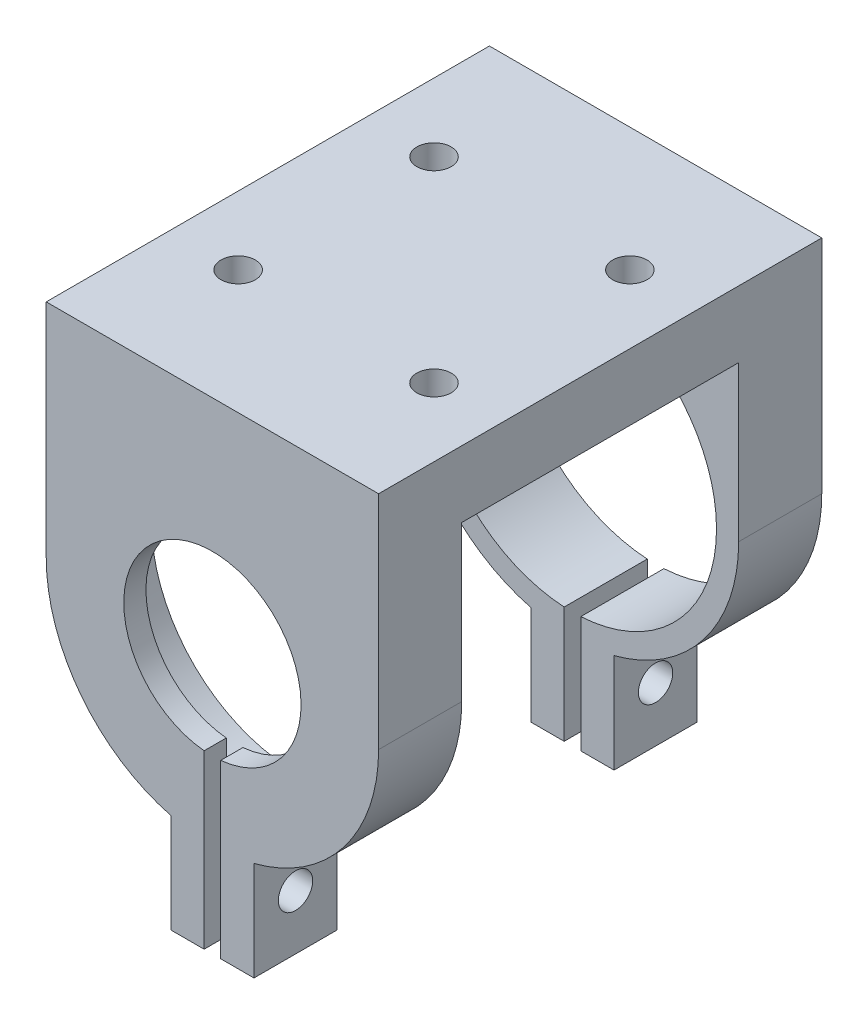
SolidWorks part; units mm, degrees
material "PLA"
ref_plane "Front Plane" through (0, 0, 0) normal (0, 0, 1) x (1, 0, 0)
ref_plane "Top Plane" through (0, 0, 0) normal (0, 1, 0) x (1, 0, 0)
ref_plane "Right Plane" through (0, 0, 0) normal (1, 0, 0) x (0, 0, -1)
sketch "Sketch1" plane through (0, 0, 0) normal (0, 0, 1) x (1, 0, 0)
  line L0 (-15, 0) -> (-15, 15)
  line L1 (-15, 15) -> (15, 15)
  line L2 (15, 15) -> (15, 0)
  line L4 (-0.75, -16.9783) -> (0.75, -16.9783)
  line L5 (-0.75, -16.9783) -> (-0.75, -12.9783)
  line L6 (-0.75, -12.9783) -> (0.75, -12.9783)
  line L7 (0.75, -16.9783) -> (0.75, -12.9783)
  line L8 (0, -44.7868) -> (0, 44.7868) construction
  circle A0 centre (0, 0) radius 13
  circle A1 centre (0, 0) radius 15
  dimension "D1" = 26
  dimension "D2" = 30
  dimension "D3" = 1.5
  dimension "D4" = 0.75
  dimension "D5" = 4
extrude "Boss-Extrude1" add sketch "Sketch1" along normal mid plane 40 contours A1 L1 L0 | A1 L2 L1 | A1 L5 A0 L7
sketch "Sketch2" plane through (0, 0, 0) normal (0, 0, 1) x (1, 0, 0)
  line L1 (-0.75, -12.9783) -> (-3.75, -12.9783)
  line L2 (-0.75, -12.9783) -> (-0.75, -23.4783)
  line L3 (-0.75, -23.4783) -> (-3.75, -23.4783)
  line L4 (-3.75, -12.9783) -> (-3.75, -23.4783)
  line L5 (0.75, -12.9783) -> (3.75, -12.9783)
  line L6 (0.75, -12.9783) -> (0.75, -23.4783)
  line L7 (0.75, -23.4783) -> (3.75, -23.4783)
  line L8 (3.75, -12.9783) -> (3.75, -23.4783)
  dimension "D1" = 3
  dimension "D2" = 10.5
extrude "Boss-Extrude2" add sketch "Sketch2" along normal mid plane 40
sketch "Sketch4" plane through (0, 15, 0) normal (0, 1, 0) x (1, 0, 0)
  line L0 (-15, -20) -> (-15, 20) construction
  line L1 (-15, 20) -> (15, 20)
  line L2 (-15, 20) -> (-15, -20)
  line L3 (-15, -20) -> (15, -20)
  line L4 (15, 20) -> (15, -20)
  line L5 (15, -20) -> (15, 20) construction
  line L6 (-44.2539, 0) -> (44.2539, 0) construction
  dimension "D1" = 40
  dimension "D2" = 20
extrude "Boss-Extrude3" add sketch "Sketch4" along normal blind 5
sketch "Sketch5" plane through (15, 0, 0) normal (1, 0, 0) x (0, 0, -1)
  line L0 (-20, -23.4783) -> (20, -23.4783) construction
  line L1 (-12.5, 14) -> (12.5, 14)
  line L2 (-12.5, 14) -> (-12.5, -23.4783)
  line L3 (-12.5, -23.4783) -> (12.5, -23.4783)
  line L4 (12.5, 14) -> (12.5, -23.4783)
  line L5 (0, 44.2539) -> (0, -44.2539) construction
  line L6 (-20, 20) -> (20, 20) construction
  dimension "D1" = 25
  dimension "D2" = 12.5
  dimension "D3" = 6
extrude "Cut-Extrude2" cut sketch "Sketch5" along direction (-1, 0, 0) on the side against the normal offset from surface (13 mm away) 2 up to plane "Right Plane"
sketch "Sketch6" plane through (0, 20, 0) normal (0, 1, 0) x (1, 0, 0)
  line L0 (-44.2539, 0) -> (44.2539, 0) construction
  line L1 (-8.8388, 8.8388) -> (8.8388, 8.8388) construction
  line L2 (-8.8388, 8.8388) -> (-8.8388, -8.8388) construction
  line L3 (-8.8388, -8.8388) -> (8.8388, -8.8388) construction
  line L4 (8.8388, 8.8388) -> (8.8388, -8.8388) construction
  line L5 (0, -44.7868) -> (0, 44.7868) construction
  circle A0 centre (-8.8388, 8.8388) radius 1.55
  circle A1 centre (8.8388, 8.8388) radius 1.55
  circle A2 centre (8.8388, -8.8388) radius 1.55
  circle A3 centre (-8.8388, -8.8388) radius 1.55
  point P6 (-8.8388, 0)
  point P7 (0, 8.8388)
  dimension "D1" = 25
  dimension "D2" = 3.1
extrude "MotorMountHoles" cut sketch "Sketch6" against normal up to surface (6 mm away) up to face at (8.5, 14, 0)
sketch "Sketch7" plane through (0, 14, 0) normal (0, -1, 0) x (1, 0, 0)
  circle A0 centre (8.8388, 8.8388) radius 2.55
  dimension "D1" = 5.1
extrude "M3ScrewHeadGuide" [suppressed] add sketch "Sketch7" along normal blind 3
sketch "Sketch8" plane through (-3.75, 0, 0) normal (-1, 0, 0) x (0, 0, 1)
  line L1 (20, -14.5237) -> (20, -23.4783) construction
  line L2 (20, -14.5237) -> (-20, -14.5237) construction
  line L3 (-12.5, -23.4783) -> (-12.5, -14.5237) construction
  line L4 (20, -14.5237) -> (-20, -14.5237) construction
  circle A0 centre (16.25, -18.5237) radius 1.55
  circle A1 centre (-16.25, -18.5237) radius 1.55
  dimension "D5" = 4
  dimension "D1" = 3.1
  dimension "D2" = 3.75
  dimension "D3" = 4
  dimension "D4" = 3.75
extrude "ClampHoles" cut sketch "Sketch8" against normal up to surface (7.5 mm away) up to face at (3.75, -19.001, 16.25)
sketch "Sketch9" plane through (0, 0, 20) normal (0, 0, 1) x (1, 0, 0)
  line L1 (-0.75, -12.9783) -> (0.75, -12.9783)
  line L2 (-0.75, -12.9783) -> (-0.75, -7.9648)
  line L3 (-0.75, -7.9648) -> (0.75, -7.9648)
  line L4 (0.75, -12.9783) -> (0.75, -7.9648)
  circle A0 centre (0, 0) radius 13
  circle A1 centre (0, 0) radius 8
  arc M13 (-0.75, -12.9783) -> (0.75, -12.9783) centre (0, 0) cw
  dimension "D1" = 16
  dimension "D2" = 26
extrude "EndStopper" add sketch "Sketch9" against normal blind 2 contours A1 L4 L2 M13
sketch "Sketch10" plane through (0, 0, 0) normal (1, 0, 0) x (0, 0, -1)
  line L1 (-12.5, 14) -> (12.5, 14)
  line L2 (-12.5, 14) -> (-12.5, -23.4783)
  line L3 (-12.5, -23.4783) -> (12.5, -23.4783)
  line L4 (12.5, 14) -> (12.5, -23.4783)
extrude "Cut-Extrude7" cut sketch "Sketch10" along normal offset from surface (13 mm away) 2 from surface at -15 up to plane "Right Plane" starting at face at (-15, 10, 0)
sketch "Sketch11" plane through (-2, 0, 0) normal (-1, 0, 0) x (0, 0, 1)
  line L1 (-12.5, -12.8452) -> (12.5, -12.8452)
  line L2 (-12.5, -12.8452) -> (-12.5, -23.4783)
  line L3 (-12.5, -23.4783) -> (12.5, -23.4783)
  line L4 (12.5, -12.8452) -> (12.5, -23.4783)
extrude "Cut-Extrude8" cut sketch "Sketch11" against normal up to surface (4 mm away) up to face at (2, -18.1618, 0)
equation "\"InnerDiam\"=26"
equation "\"D1@Sketch1\"=\"InnerDiam\""
equation "\"OuterDiam\"=30"
equation "\"D2@Sketch1\"=\"OuterDiam\""
equation "\"TightenGap\"=1.5"
equation "\"D3@Sketch1\"=\"TightenGap\""
equation "\"D4@Sketch1\"=\"TightenGap\"/2"
equation "\"D5@Sketch1\"=\"OuterDiam\"-\"InnerDiam\""
equation "\"ClampLen\"=10.5"
equation "\"D2@Sketch2\"=\"ClampLen\""
equation "\"Thick\"=40"
equation "\"D1@Boss-Extrude2\"=\"Thick\""
equation "\"D1@Boss-Extrude1\"=\"Thick\""
equation "\"MotBaseThick\"=5"
equation "\"D1@Boss-Extrude3\"=\"MotBaseThick\""
equation "\"TopPlateLen\"=35"
equation "\"D1@Sketch4\"=\"Thick\""
equation "\"D2@Sketch4\"=\"Thick\"/2"
equation "\"D1@Sketch5\"=\"Thick\"- 2 * \"ClampWidth\""
equation "\"D2@Sketch5\"=(\"Thick\"- 2 * \"ClampWidth\")/2"
equation "\"MotorMountDiam\"=25"
equation "\"D1@Sketch6\"=\"MotorMountDiam\""
equation "\"ClampWidth\"= 7.5"
equation "\"D2@Sketch8\"=\"ClampWidth\"/2"
equation "\"D3@Sketch8\"=(\"ClampLen\"- 2.5)/2"
equation "\"D4@Sketch8\"=\"ClampWidth\"/2"
equation "\"D5@Sketch8\"=(\"ClampLen\"- 2.5)/2"
equation "\"D2@Sketch9\"=\"InnerDiam\""
equation "\"D19@Cut-Extrude2\"=\"OuterDiam\"/2"
